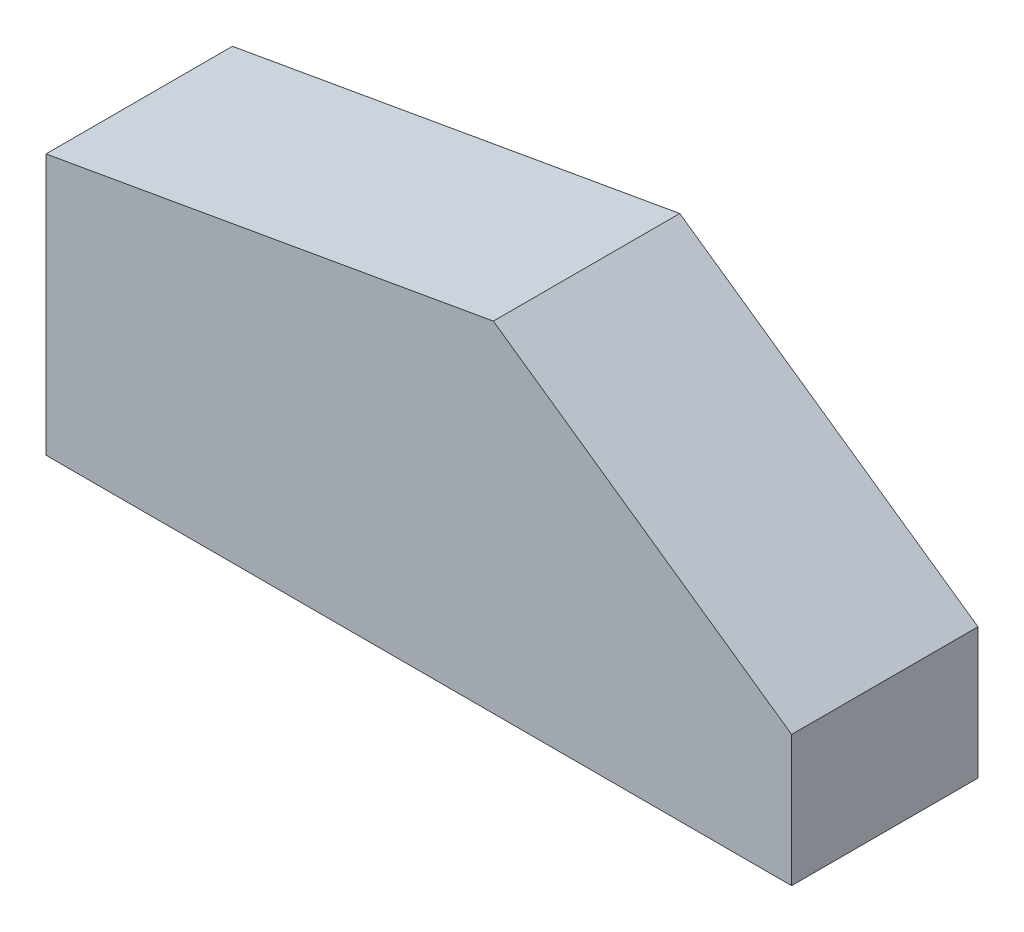
SolidWorks part; units mm, degrees
ref_plane "Front Plane" through (0, 0, 0) normal (0, 0, 1) x (1, 0, 0)
ref_plane "Top Plane" through (0, 0, 0) normal (0, 1, 0) x (1, 0, 0)
ref_plane "Right Plane" through (0, 0, 0) normal (1, 0, 0) x (0, 0, -1)
sketch "Sketch1" plane through (0, 0, 0) normal (0, 0, 1) x (1, 0, 0)
  line L0 (0, 0) -> (0, 35)
  line L1 (0, 35) -> (60, 45.5796)
  line L2 (60, 45.5796) -> (100, 17.5713)
  line L3 (100, 17.5713) -> (100, 0)
  line L4 (100, 0) -> (0, 0)
  dimension "D1" = 100
  dimension "D2" = 35
  dimension "D3" = 60
  dimension "D4" = 100
  dimension "D5" = 135
extrude "Boss-Extrude1" add sketch "Sketch1" along normal blind 25
